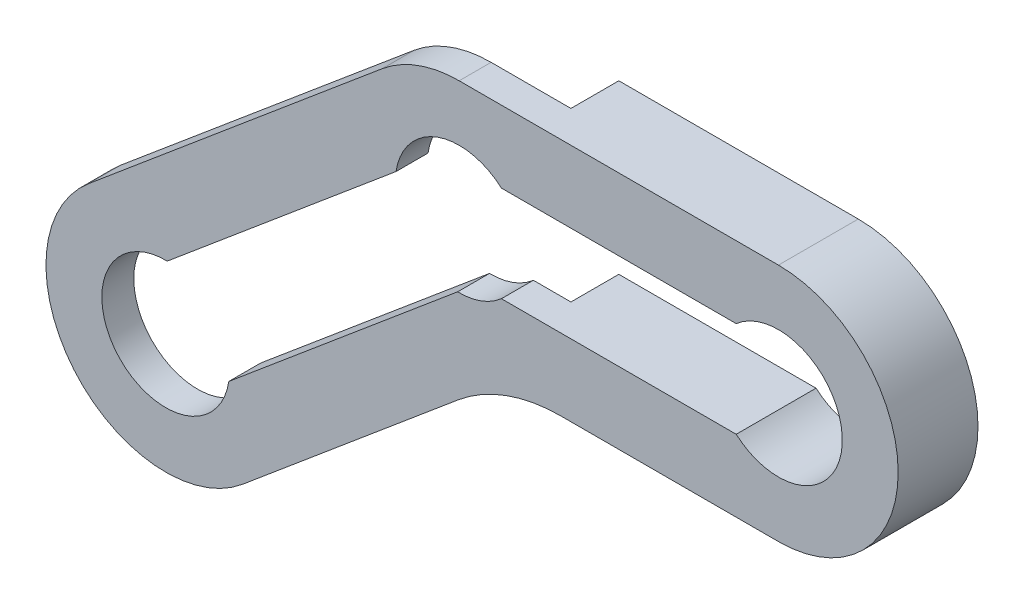
SolidWorks part; units mm, degrees
ref_plane "Спереди" through (0, 0, 0) normal (0, 0, 1) x (1, 0, 0)
ref_plane "Сверху" through (0, 0, 0) normal (0, 1, 0) x (1, 0, 0)
ref_plane "Справа" through (0, 0, 0) normal (1, 0, 0) x (0, 0, -1)
sketch "Эскиз1" plane through (0, 0, 0) normal (0, 0, 1) x (1, 0, 0)
  line L0 (0, 0) -> (-20, 0) construction
  line L1 (-20, 0) -> (-38.3851, -15.4269) construction
  line L2 (0, 7.5) -> (-20, 7.5)
  line L3 (0, -7.5) -> (-20, -7.5)
  line L4 (-43.206, -9.6816) -> (-24.8209, 5.7453)
  line L5 (-33.5642, -21.1722) -> (-15.1791, -5.7453)
  circle A0 centre (0, 0) radius 7.5
  circle A1 centre (-38.3851, -15.4269) radius 7.5
  circle A2 centre (-20, 0) radius 7.5
  circle A3 centre (0, 0) radius 4
  circle A4 centre (-20, 0) radius 4
  circle A5 centre (-38.3851, -15.4269) radius 4
  dimension "D1" = 15
  dimension "D5" = 15
  dimension "D6" = 8
  dimension "D7" = 8
  dimension "D8" = 8
  dimension "D2" = 140
  dimension "D3" = 20
  dimension "D4" = 24
extrude "Бобышка-Вытянуть1" add sketch "Эскиз1" along normal blind 2 contours A1 A5 | A2 L4 A1 L5 L3 | A2 A4 | A2 L3 L5 | A2 L5 L3 A0 L2 | A0 A3
fillet "Скругление1" radius 10 1 edges at (-17.2702, -7.5, 1)
sketch "Эскиз2" plane through (0, 0, 0) normal (0, 0, -1) x (-1, 0, 0)
  line L0 (0, -7.5) -> (15, -7.5)
  line L1 (0, -7.5) -> (13.6305, -7.5) construction
  line L2 (15, -7.5) -> (15, 7.5)
  line L3 (0, 7.5) -> (20, 7.5) construction
  line L4 (15, 7.5) -> (0, 7.5)
  arc A0 (0, 7.5) -> (0, -7.5) centre (0, 0) ccw construction
  arc A1 (0, 7.5) -> (0, -7.5) centre (0, 0) ccw
  circle A2 centre (0, 0) radius 4 construction
  circle A3 centre (0, 0) radius 4
  dimension "D1" = 15
extrude "Бобышка-Вытянуть2" add sketch "Эскиз2" along normal blind 3
sketch "Эскиз4" plane through (0, 0, 2) normal (0, 0, 1) x (1, 0, 0)
  line L0 (-38.3851, -15.4269) -> (-20, 0) construction
  line L1 (-40.3134, -13.1288) -> (-21.9284, 2.2981)
  line L2 (-36.4567, -17.725) -> (-18.0716, -2.2981)
  line L3 (-20, 0) -> (0, 0) construction
  line L4 (-20, 3) -> (0, 3)
  line L5 (-20, -3) -> (0, -3)
  arc A0 (-40.3134, -13.1288) -> (-36.4567, -17.725) centre (-38.3851, -15.4269) ccw
  arc A1 (-18.0716, -2.2981) -> (-21.9284, 2.2981) centre (-20, 0) ccw
  arc A2 (-20, 3) -> (-20, -3) centre (-20, 0) ccw
  arc A3 (0, -3) -> (0, 3) centre (0, 0) ccw
  point P4 (-29.1925, -7.7135)
  point P12 (-10, 0)
  circle M9 centre (-38.3851, -15.4269) radius 4
  circle M10 centre (-20, 0) radius 4
  circle M11 centre (0, 0) radius 4
  dimension "D1" = 6
extrude "Вырез-Вытянуть1" cut sketch "Эскиз4" against normal through all contours L2 L1 M9 M10 | L5 L4 M10 M11
